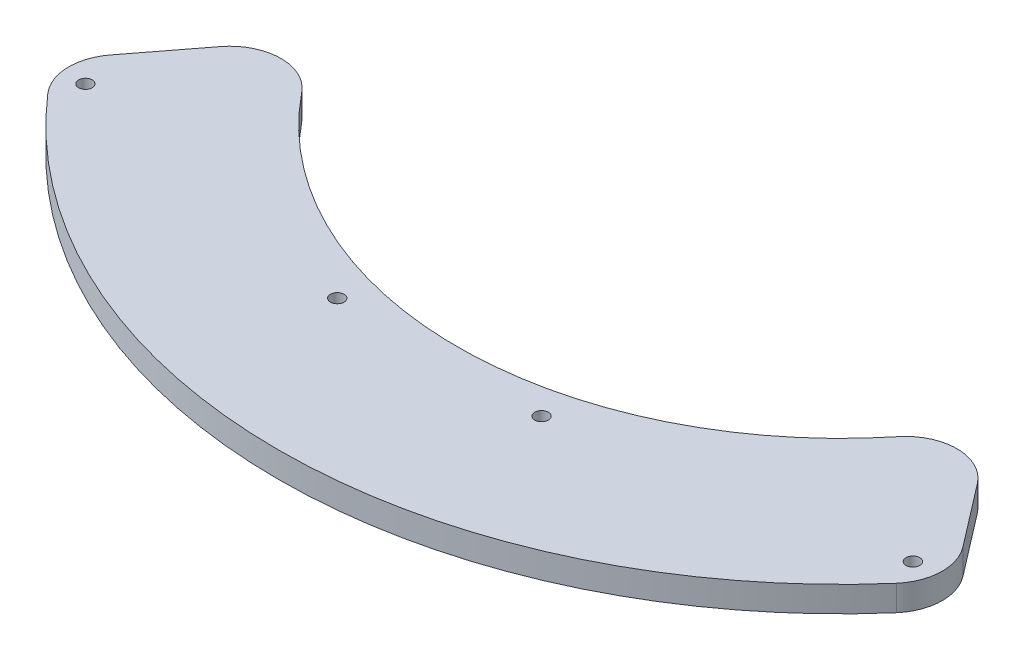
SolidWorks part; units mm, degrees
ref_plane "Front Plane" through (0, 0, 0) normal (0, 0, 1) x (1, 0, 0)
ref_plane "Top Plane" through (0, 0, 0) normal (0, 1, 0) x (1, 0, 0)
ref_plane "Right Plane" through (0, 0, 0) normal (1, 0, 0) x (0, 0, -1)
sketch "Sketch1" plane through (0, 0, 0) normal (0, 1, 0) x (1, 0, 0)
  line L0 (0, 0) -> (0, -152.4) construction
  line L1 (-152.4, -152.4) -> (152.4, -152.4) construction
  line L2 (-152.4, -152.4) -> (-152.4, 152.4) construction
  line L3 (-152.4, 152.4) -> (152.4, 152.4) construction
  line L4 (152.4, -152.4) -> (152.4, 152.4) construction
  line L5 (-152.4, -152.4) -> (152.4, 152.4) construction
  line L6 (-152.4, 152.4) -> (152.4, -152.4) construction
  line L7 (0, 0) -> (0, 102.2502) construction
  line L8 (0, 102.2502) -> (65.7158, 16.6077) construction
  line L9 (143.0285, -84.1481) -> (65.7158, 16.6077) construction
  line L10 (50.6024, 5.0108) -> (80.8292, 28.2047) construction
  line L11 (50.6024, 5.0108) -> (127.9151, -95.745) construction
  line L12 (127.9151, -95.745) -> (158.1419, -72.5512) construction
  line L13 (80.8292, 28.2047) -> (158.1419, -72.5512) construction
  line L14 (0, 102.2502) -> (50.1691, -133.7768) construction
  line L15 (50.1691, -133.7768) -> (68.8028, -129.8161) construction
  line L16 (68.8028, -129.8161) -> (42.398, -5.5913) construction
  line L17 (42.398, -5.5913) -> (5.1306, -13.5127) construction
  line L18 (5.1306, -13.5127) -> (31.5354, -137.7375) construction
  line L19 (31.5354, -137.7375) -> (50.1691, -133.7768) construction
  line L20 (0, 102.2502) -> (-65.7158, 16.6077) construction
  line L21 (-50.6024, 5.0108) -> (-80.8292, 28.2047) construction
  line L22 (-127.9151, -95.745) -> (-158.1419, -72.5512) construction
  line L23 (-80.8292, 28.2047) -> (-158.1419, -72.5512) construction
  line L24 (-50.6024, 5.0108) -> (-127.9151, -95.745) construction
  line L25 (-143.0285, -84.1481) -> (-65.7158, 16.6077) construction
  line L26 (-31.5354, -137.7375) -> (-50.1691, -133.7768) construction
  line L27 (-50.1691, -133.7768) -> (-68.8028, -129.8161) construction
  line L28 (-42.398, -5.5913) -> (-5.1306, -13.5127) construction
  line L29 (-5.1306, -13.5127) -> (-31.5354, -137.7375) construction
  line L30 (0, 102.2502) -> (-50.1691, -133.7768) construction
  line L31 (-68.8028, -129.8161) -> (-42.398, -5.5913) construction
  line L32 (0, 102.2502) -> (-152.4, -101.762) construction
  line L33 (0, 102.2502) -> (-112.0468, 18.8141) construction
  line L34 (0, 102.2502) -> (112.0468, 18.8141) construction
  line L35 (-105.9774, 26.7239) -> (-94.0975, 42.206)
  line L36 (94.0975, 42.206) -> (105.9774, 26.7239)
  line L37 (0, 102.2502) -> (152.4, -101.762) construction
  line L38 (-152.4, -50.962) -> (-152.4, -101.762) construction
  line L39 (152.4, -50.962) -> (152.4, -101.762) construction
  line L40 (72.5295, -129.0239) -> (45.3326, -1.0724) construction
  line L41 (45.3326, -1.0724) -> (0.6117, -10.5781) construction
  line L42 (0.6117, -10.5781) -> (27.8086, -138.5296) construction
  line L43 (81.5325, 33.5467) -> (161.1646, -70.2318) construction
  line L44 (45.2604, 5.7141) -> (81.5325, 33.5467) construction
  line L45 (45.2604, 5.7141) -> (124.8924, -98.0644) construction
  line L46 (98.1127, 11.939) -> (81.5325, 33.5467) construction
  line L47 (81.5325, 33.5467) -> (63.3964, 19.6304) construction
  line L48 (63.3964, 19.6304) -> (57.9845, 26.6833) construction
  line L49 (100.7298, 33.5626) -> (94.0975, 42.206) construction
  line L50 (91.0399, 21.1564) -> (81.5325, 33.5467) construction
  line L51 (81.5325, 33.5467) -> (63.3964, 19.6304) construction
  line L52 (54.7678, -6.6762) -> (45.2604, 5.7141) construction
  line L53 (45.2604, 5.7141) -> (63.3964, 19.6304) construction
  line L54 (47.2595, -10.1376) -> (45.3326, -1.0724) construction
  line L55 (45.3326, -1.0724) -> (0.6117, -10.5781) construction
  line L56 (-0.6117, -10.5781) -> (0.6117, -10.5781) construction
  line L57 (-100.7298, 33.5626) -> (-94.0975, 42.206) construction
  line L58 (-91.0399, 21.1564) -> (-81.5325, 33.5467) construction
  line L59 (-81.5325, 33.5467) -> (-63.3964, 19.6304) construction
  line L60 (-45.2604, 5.7141) -> (-63.3964, 19.6304) construction
  line L61 (-54.7678, -6.6762) -> (-45.2604, 5.7141) construction
  line L62 (-47.2595, -10.1376) -> (-45.3326, -1.0724) construction
  line L63 (-45.3326, -1.0724) -> (-0.6117, -10.5781) construction
  circle A0 centre (0, 102.2502) radius 12.7 construction
  arc A1 (-152.4, -101.762) -> (152.4, -101.762) centre (0, 102.2502) ccw construction
  arc A2 (-152.4, -50.962) -> (152.4, -50.962) centre (0, 102.2502) ccw construction
  arc A3 (-105.492, 10.6668) -> (105.492, 10.6668) centre (0, 102.2502) ccw
  arc A4 (-74.137, 42.4484) -> (74.137, 42.4484) centre (0, 102.2502) ccw
  arc A5 (74.137, 42.4484) -> (94.0975, 42.206) centre (84.0219, 34.4748) cw
  arc A6 (-74.137, 42.4484) -> (-94.0975, 42.206) centre (-84.0219, 34.4748) ccw
  arc A7 (105.9774, 26.7239) -> (105.492, 10.6668) centre (95.9018, 18.9926) cw
  arc A8 (-105.9774, 26.7239) -> (-105.492, 10.6668) centre (-95.9018, 18.9926) ccw
  arc A9 (-97.8072, 11.6082) -> (110.1733, 27.1232) centre (0, 102.2502) ccw construction
  circle A10 centre (102.87, 17.3975) radius 1.7005
  circle A11 centre (83.82, 40.64) radius 1.7005 construction
  circle A12 centre (25.4, 2.54) radius 1.7005
  circle A13 centre (0, -30.48) radius 1.7005 construction
  circle A14 centre (-102.87, 17.3975) radius 1.7005
  circle A15 centre (-83.82, 40.64) radius 1.7005 construction
  circle A16 centre (-25.4, 2.54) radius 1.7005
  arc A17 (74.137, 42.4484) -> (-74.137, 42.4484) centre (0, 102.2502) cw construction
  arc A18 (-89.4237, 19.3775) -> (100.7298, 33.5626) centre (0, 102.2502) ccw construction
  arc A19 (91.0399, 21.1564) -> (100.7298, 33.5626) centre (0, 102.2502) ccw construction
  arc A20 (94.0975, 42.206) -> (74.137, 42.4484) centre (84.0219, 34.4748) ccw construction
  arc A21 (54.7678, -6.6762) -> (47.2595, -10.1376) centre (0, 102.2502) cw construction
  circle A22 centre (0, 0) radius 1.7005 construction
  circle A23 centre (-83.82, 40.64) radius 1.7005 construction
  arc A24 (-94.0975, 42.206) -> (-74.137, 42.4484) centre (-84.0219, 34.4748) cw construction
  arc A25 (-91.0399, 21.1564) -> (-100.7298, 33.5626) centre (0, 102.2502) cw construction
  arc A26 (-54.7678, -6.6762) -> (-47.2595, -10.1376) centre (0, 102.2502) ccw construction
  point P0 (0, 0)
  point P60 (98.1127, 11.939)
  dimension "D4" = 25.4
  dimension "D19" = 12.7
  dimension "D13" = 139.7
  dimension "D14" = 95.25
  dimension "D18" = 12.7
  dimension "D21" = 133.35
  dimension "D22" = 3.4011
  dimension "D28" = 30.48
  dimension "D17" = 3.4011
  dimension "D1" = 304.8
  dimension "D2" = 304.8
  dimension "D3" = 50.1498
  dimension "D5" = 127
  dimension "D6" = 38.1
  dimension "D7" = 37.5
  dimension "D8" = 107.95
  dimension "D9" = 12
  dimension "D10" = 38.1
  dimension "D11" = 127
  dimension "D12" = 114.3
  dimension "D15" = 19.05
  dimension "D16" = 50.8
  dimension "D20" = 3.81
  dimension "D23" = 102.87
  dimension "D24" = 83.82
  dimension "D25" = 40.64
  dimension "D26" = 25.4
  dimension "D27" = 2.54
  dimension "D30" = 11.8077
  dimension "D29" = 11.43
extrude "Boss-Extrude1" add sketch "Sketch1" along normal blind 6.35
